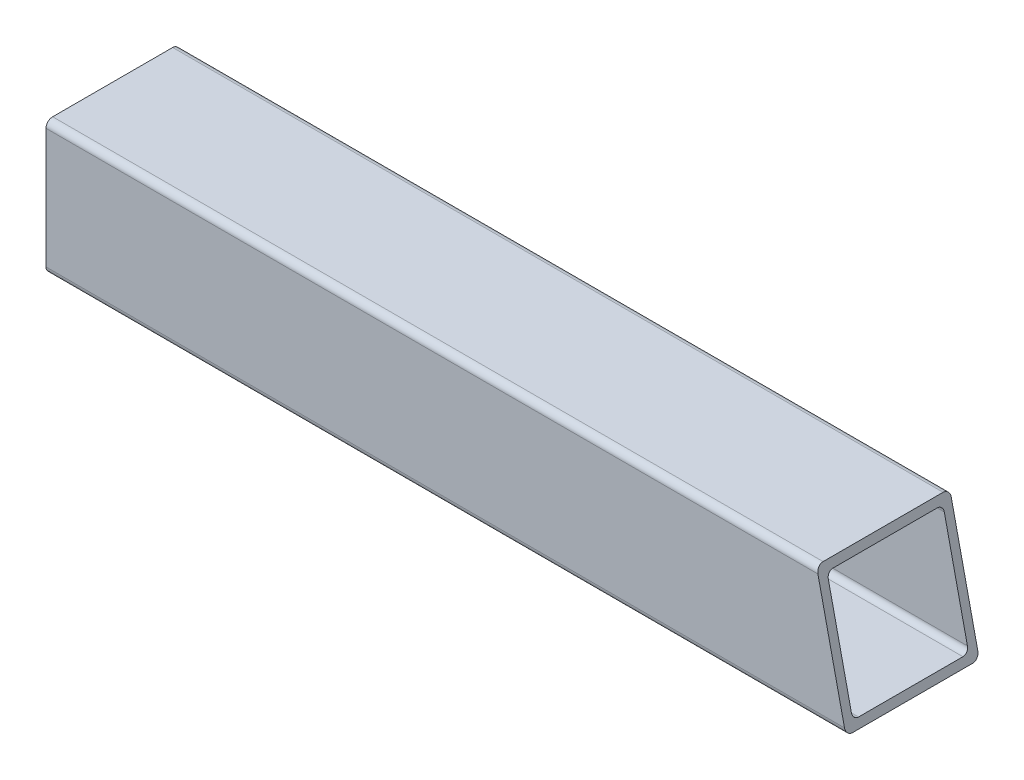
SolidWorks part; units mm, degrees
ref_plane "Front" through (0, 0, 0) normal (0, 0, 1) x (1, 0, 0)
ref_plane "Top" through (0, 0, 0) normal (0, 1, 0) x (1, 0, 0)
ref_plane "Right" through (0, 0, 0) normal (1, 0, 0) x (0, 0, -1)
sketch "Sketch1" plane through (0, 0, 0) normal (1, 0, 0) x (0, 0, -1)
  line L0 (-11.049, 0) -> (-12.7, 0) construction
  line L1 (11.43, -12.7) -> (-11.43, -12.7) construction
  line L2 (12.7, -11.43) -> (12.7, 11.43) construction
  line L3 (11.43, 12.7) -> (-11.43, 12.7) construction
  line L4 (-12.7, -11.43) -> (-12.7, 11.43) construction
  line L5 (12.7, -12.7) -> (-12.7, 12.7) construction
  line L6 (12.7, 12.7) -> (-12.7, -12.7) construction
  line L7 (9.9441, 11.049) -> (-9.9441, 11.049) construction
  line L8 (11.049, 9.9441) -> (11.049, -9.9441) construction
  line L9 (9.9441, -11.049) -> (-9.9441, -11.049) construction
  line L10 (-11.049, 9.9441) -> (-11.049, -9.9441) construction
  line L11 (11.049, 11.049) -> (-11.049, -11.049) construction
  line L12 (11.049, -11.049) -> (-11.049, 11.049) construction
  line L13 (0, -11.049) -> (0, -12.7) construction
  line L14 (11.049, -9.9441) -> (11.049, -12.7) construction
  line L15 (11.049, 0) -> (12.7, 0) construction
  line L16 (11.049, -12.7) -> (12.7, -12.7) construction
  arc A0 (-9.9441, -11.049) -> (-11.049, -9.9441) centre (-9.9441, -9.9441) cw construction
  arc A1 (11.049, -9.9441) -> (9.9441, -11.049) centre (9.9441, -9.9441) cw construction
  arc A2 (9.9441, 11.049) -> (11.049, 9.9441) centre (9.9441, 9.9441) cw construction
  arc A3 (-9.9441, 11.049) -> (-11.049, 9.9441) centre (-9.9441, 9.9441) ccw construction
  arc A4 (11.43, -12.7) -> (12.7, -11.43) centre (11.43, -11.43) ccw construction
  arc A5 (12.7, 11.43) -> (11.43, 12.7) centre (11.43, 11.43) ccw construction
  arc A6 (-11.43, 12.7) -> (-12.7, 11.43) centre (-11.43, 11.43) ccw construction
  arc A7 (-11.43, -12.7) -> (-12.7, -11.43) centre (-11.43, -11.43) cw construction
  point P0 (0, 0)
  point P6 (0, 0)
  dimension "D2" = 1.1049
  dimension "D3" = 1.27
  dimension "Outside Width" = 25.4
  dimension "Ouside Height" = 25.4
  dimension "Inside Height" = 22.098
  dimension "Wall Thickness" = 1.651
sketch "Sketch2" plane through (0, 0, 0) normal (0, 0, 1) x (1, 0, 0)
  line L0 (-76.2, 0) -> (76.2, 0) construction
  point P3 (-52.451, 0)
  point P4 (52.451, 0)
  dimension "Length" = 152.4
  dimension "D1" = 23.749
  dimension "D2" = 23.749
sketch "Sketch4" plane through (0, 0, 0) normal (1, 0, 0) x (0, 0, -1)
  line L8 (12.7, -11.43) -> (12.7, 11.43)
  line L9 (11.43, 12.7) -> (-11.43, 12.7)
  line L10 (-12.7, -11.43) -> (-12.7, 11.43)
  line L11 (11.43, -12.7) -> (-11.43, -12.7)
  line L12 (11.049, 9.9441) -> (11.049, -9.9441)
  line L13 (9.9441, -11.049) -> (-9.9441, -11.049)
  line L14 (-11.049, 9.9441) -> (-11.049, -9.9441)
  line L15 (9.9441, 11.049) -> (-9.9441, 11.049)
  arc A8 (12.7, 11.43) -> (11.43, 12.7) centre (11.43, 11.43) ccw
  arc A9 (-11.43, 12.7) -> (-12.7, 11.43) centre (-11.43, 11.43) ccw
  arc A10 (-12.7, -11.43) -> (-11.43, -12.7) centre (-11.43, -11.43) ccw
  arc A11 (11.43, -12.7) -> (12.7, -11.43) centre (11.43, -11.43) ccw
  arc A12 (9.9441, -11.049) -> (11.049, -9.9441) centre (9.9441, -9.9441) ccw
  arc A13 (-11.049, -9.9441) -> (-9.9441, -11.049) centre (-9.9441, -9.9441) ccw
  arc A14 (-9.9441, 11.049) -> (-11.049, 9.9441) centre (-9.9441, 9.9441) ccw
  arc A15 (11.049, 9.9441) -> (9.9441, 11.049) centre (9.9441, 9.9441) ccw
extrude "Boss-Extrude1" add sketch "Sketch4" along normal up to vertex (76.2 mm away) and the other way up to vertex (76.2 mm away)
sketch "Sketch5" plane through (0, 0, 12.7) normal (0, 0, 1) x (1, 0, 0)
  line L0 (76.2, -12.7) -> (70.569, 12.7)
  line L1 (76.2, 12.7) -> (-76.2, 12.7) construction
  line L2 (70.569, 12.7) -> (76.2, 12.7)
  line L3 (76.2, 12.7) -> (76.2, -12.7)
  dimension "D1" = 12.5
extrude "Cut-Extrude1" cut sketch "Sketch5" against normal through all
equation "\"D3@Sketch1\"=\"Outside Width@Sketch1\"*.05"
equation "\"D2@Sketch1\" = \"Inside Height@Sketch1\" * .05"
equation "\"D1@Sketch2\"=\"Outside Width@Sketch1\"-\"Wall Thickness@Sketch1\""
equation "\"D2@Sketch2\"=\"D1@Sketch2\""
